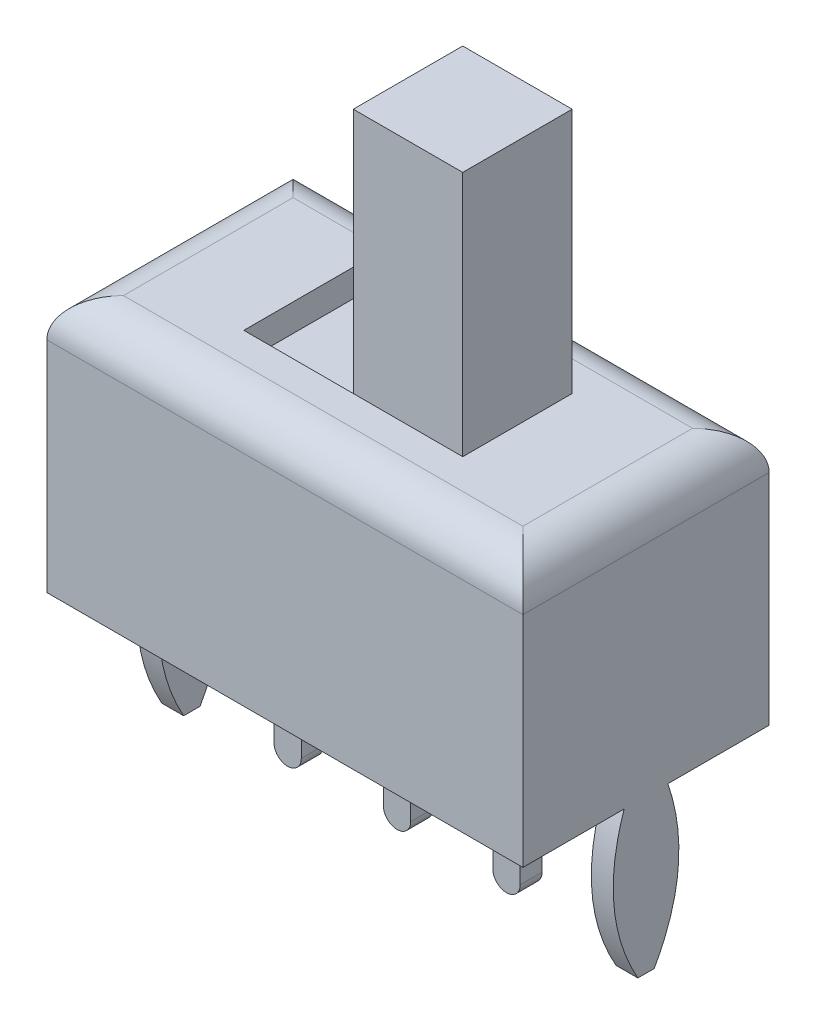
SolidWorks part; units mm, degrees
ref_plane "Front Plane" through (0, 0, 0) normal (0, 0, 1) x (1, 0, 0)
ref_plane "Top Plane" through (0, 0, 0) normal (0, 1, 0) x (1, 0, 0)
ref_plane "Right Plane" through (0, 0, 0) normal (1, 0, 0) x (0, 0, -1)
sketch "Sketch1" plane through (0, 0, 0) normal (0, 0, 1) x (1, 0, 0)
  line L1 (-4.35, 2.35) -> (4.35, 2.35)
  line L2 (-4.35, 2.35) -> (-4.35, -2.35)
  line L3 (-4.35, -2.35) -> (4.35, -2.35)
  line L4 (4.35, 2.35) -> (4.35, -2.35)
  line L5 (-4.35, 2.35) -> (4.35, -2.35) construction
  line L6 (-4.35, -2.35) -> (4.35, 2.35) construction
  point P0 (0, 0)
  dimension "D1" = 8.7
  dimension "D2" = 4.7
extrude "Boss-Extrude1" add sketch "Sketch1" along normal mid plane 4.5
fillet "Fillet1" radius 0.7 4 edges at (4.35, 2.35, 0) (0, 2.35, -2.25) (0, 2.35, 2.25) (-4.35, 2.35, 0)
sketch "Sketch3" plane through (-4.35, 0, 0) normal (-1, 0, 0) x (0, 0, 1)
  line L0 (0, -2.35) -> (0, -5.15) construction
  line L1 (2.25, -2.35) -> (-2.25, -2.35) construction
  line L2 (-0.15, -5.15) -> (0.15, -5.15)
  line L3 (-0.4, -2.35) -> (0.4, -2.35)
  line L4 (-1.55, 2.35) -> (1.55, 2.35) construction
  line L5 (0.6, -2.35) -> (0.6, -5.1693) construction
  spline S0 degree 2 poles (0.4, -2.35) (0.9, -3.8201) (0.15, -5.15) knots 0 0 0 1 1 1
  spline S1 degree 2 poles (-0.4, -2.35) (-0.9, -3.8201) (-0.15, -5.15) knots 0 0 0 1 1 1
  point P11 (2.7873, -4.4321)
  point P12 (2.7001, -4.8295)
  point P13 (0, 0)
  dimension "D1" = 0.15
  dimension "D2" = 7.5
  dimension "D3" = 0.6
  dimension "D4" = 0.4
extrude "Boss-Extrude2" add sketch "Sketch3" against normal blind 0.4
mirror "Mirror1" about plane through (0, 0, 0) normal (1, 0, 0) of "Boss-Extrude2"
sketch "Sketch5" plane through (0, 0, 0) normal (0, 0, 1) x (1, 0, 0)
  line L0 (0, -2.35) -> (0, -4.7) construction
  line L1 (-4.35, -2.35) -> (4.35, -2.35) construction
  line L2 (-0.25, -2.35) -> (0.25, -2.35)
  line L3 (0.25, -2.35) -> (0.25, -4.7)
  line L4 (0, -4.7) -> (0, -4.95) construction
  line L6 (-0.25, -2.35) -> (-0.25, -4.7)
  line L7 (-3.65, 2.35) -> (3.65, 2.35) construction
  line L8 (1.75, -2.35) -> (2.25, -2.35)
  line L9 (2.25, -2.35) -> (2.25, -4.7)
  line L10 (1.75, -2.35) -> (1.75, -4.7)
  line L11 (-1.75, -2.35) -> (-1.75, -4.7)
  line L12 (-2.25, -2.35) -> (-2.25, -4.7)
  line L13 (-1.75, -2.35) -> (-2.25, -2.35)
  arc A0 (0.25, -4.7) -> (-0.25, -4.7) centre (0, -4.7) cw
  arc A1 (2.25, -4.7) -> (1.75, -4.7) centre (2, -4.7) cw
  arc A2 (-2.25, -4.7) -> (-1.75, -4.7) centre (-2, -4.7) ccw
  point P12 (2.3966, -2.35)
  point P13 (1.6718, -2.35)
  point P19 (2, -2.35)
  dimension "D1" = 0.25
  dimension "D2" = 7.3
  dimension "D4" = 2
  dimension "D3" = 2
extrude "Boss-Extrude3" add sketch "Sketch5" along normal mid plane 0.4
sketch "Sketch6" plane through (0, 2.35, 0) normal (0, 1, 0) x (1, 0, 0)
  line L1 (-2, 1) -> (2, 1)
  line L2 (-2, 1) -> (-2, -1)
  line L3 (-2, -1) -> (2, -1)
  line L4 (2, 1) -> (2, -1)
  line L5 (-2, 1) -> (2, -1) construction
  line L6 (-2, -1) -> (2, 1) construction
  point P0 (0, 0)
  dimension "D1" = 2
  dimension "D2" = 4
extrude "Cut-Extrude1" cut sketch "Sketch6" against normal blind 0.5
sketch "Sketch7" plane through (0, 1.85, 0) normal (0, 1, 0) x (1, 0, 0)
  line L0 (-2, -1) -> (2, -1) construction
  line L1 (2, 1) -> (0, 1)
  line L2 (2, 1) -> (2, -1)
  line L3 (2, -1) -> (0, -1)
  line L4 (0, 1) -> (0, -1)
extrude "Boss-Extrude4" add sketch "Sketch7" along normal blind 5
